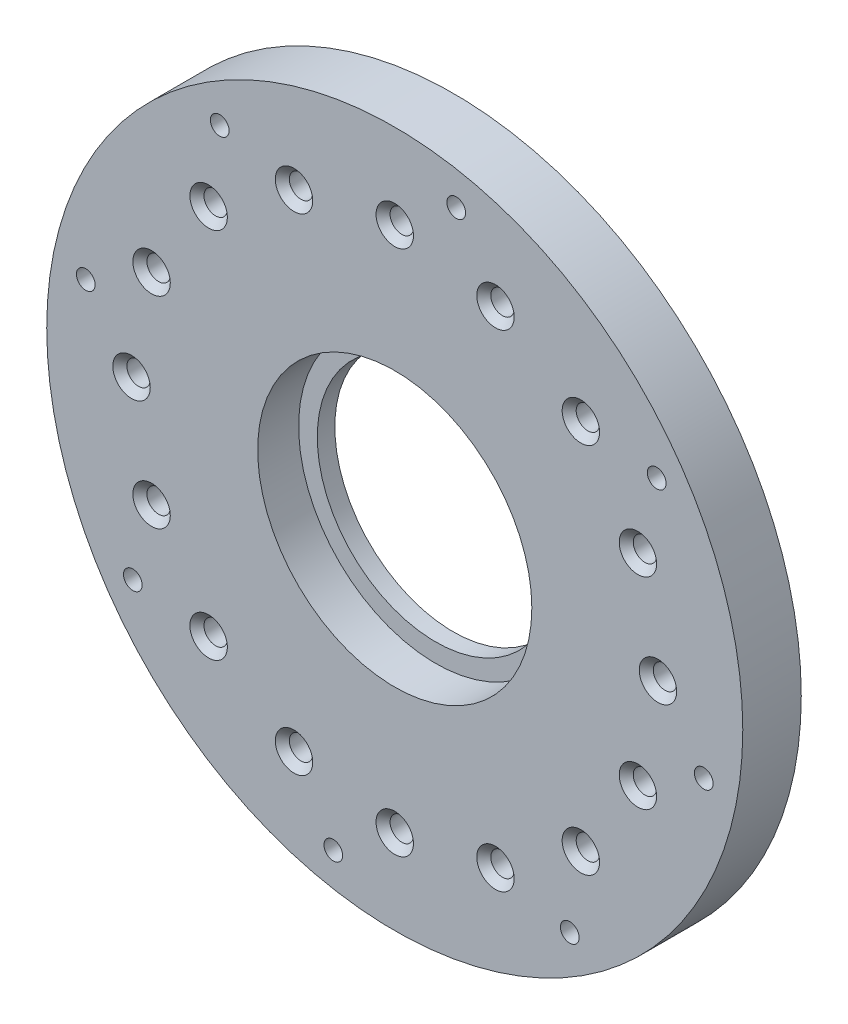
SolidWorks part; units mm, degrees
ref_plane "Front Plane" through (0, 0, 0) normal (0, 0, 1) x (1, 0, 0)
ref_plane "Top Plane" through (0, 0, 0) normal (0, 1, 0) x (1, 0, 0)
ref_plane "Right Plane" through (0, 0, 0) normal (1, 0, 0) x (0, 0, -1)
sketch "Sketch3" plane through (0, 0, 0) normal (0, 0, 1) x (1, 0, 0)
  circle A0 centre (0, 0) radius 59.5
  dimension "D1" = 119
extrude "Boss-Extrude1" add sketch "Sketch3" along normal blind 10
sketch "Sketch4" plane through (0, 0, 10) normal (0, 0, 1) x (1, 0, 0)
  line L0 (0, 0) -> (80.3371, 0) construction
  line L1 (0, 0) -> (65.7826, 43.9545) construction
  circle A0 centre (0, 0) radius 53.86 construction
  circle A1 centre (44.783, 29.923) radius 1.6
  circle A2 centre (52.8251, -10.5076) radius 1.6
  circle A3 centre (29.923, -44.783) radius 1.6
  circle A4 centre (-10.5076, -52.8251) radius 1.6
  circle A5 centre (-44.783, -29.923) radius 1.6
  circle A6 centre (-52.8251, 10.5076) radius 1.6
  circle A7 centre (-29.923, 44.783) radius 1.6
  circle A8 centre (10.5076, 52.8251) radius 1.6
  point P5 (44.783, 29.923)
  point P25 (0, 0)
  dimension "D1" = 107.72
  dimension "D2" = 3.2
  dimension "D3" = 8
extrude "Cut-Extrude1" cut sketch "Sketch4" against normal through all
sketch "Sketch5" plane through (0, 0, 10) normal (0, 0, 1) x (1, 0, 0)
  line L0 (0, 0) -> (91.3259, 0) construction
  circle A0 centre (0, 0) radius 45 construction
  circle A1 centre (45, 0) radius 2
  circle A2 centre (41.5746, -17.2208) radius 2
  circle A3 centre (31.8198, -31.8198) radius 2
  circle A4 centre (17.2208, -41.5746) radius 2
  circle A5 centre (0, -45) radius 2
  circle A6 centre (-17.2208, -41.5746) radius 2
  circle A7 centre (-31.8198, -31.8198) radius 2
  circle A8 centre (-41.5746, -17.2208) radius 2
  circle A9 centre (-45, 0) radius 2
  circle A10 centre (-41.5746, 17.2208) radius 2
  circle A11 centre (-31.8198, 31.8198) radius 2
  circle A12 centre (-17.2208, 41.5746) radius 2
  circle A13 centre (0, 45) radius 2
  circle A14 centre (17.2208, 41.5746) radius 2
  circle A15 centre (31.8198, 31.8198) radius 2
  circle A16 centre (41.5746, 17.2208) radius 2
  point P38 (0, 0)
  dimension "D1" = 90
  dimension "D2" = 4
  dimension "D3" = 16
extrude "Cut-Extrude2" cut sketch "Sketch5" against normal blind 5
sketch "Sketch6" plane through (0, 0, 0) normal (0, 0, -1) x (-1, 0, 0)
  line L0 (0, 0) -> (52.8251, 10.5076) construction
  circle A0 centre (52.8251, 10.5076) radius 2.9
  circle A1 centre (44.783, -29.923) radius 2.9
  circle A2 centre (10.5076, -52.8251) radius 2.9
  circle A3 centre (-29.923, -44.783) radius 2.9
  circle A4 centre (-52.8251, -10.5076) radius 2.9
  circle A5 centre (-44.783, 29.923) radius 2.9
  circle A6 centre (-10.5076, 52.8251) radius 2.9
  circle A7 centre (29.923, 44.783) radius 2.9
  point P22 (0, 0)
  dimension "D1" = 5.8
  dimension "D2" = 8
extrude "Cut-Extrude3" cut sketch "Sketch6" against normal blind 3
sketch "Sketch7" plane through (0, 0, 10) normal (0, 0, 1) x (1, 0, 0)
  circle A0 centre (0, 0) radius 23.435
  dimension "D1" = 46.87
extrude "Cut-Extrude4" cut sketch "Sketch7" against normal blind 7
sketch "Sketch8" plane through (0, 0, 10) normal (0, 0, 1) x (1, 0, 0)
  circle A0 centre (0, 0) radius 20.25
  dimension "D1" = 40.5
extrude "Cut-Extrude5" cut sketch "Sketch8" against normal through all
chamfer "Chamfer1" distance 1.2 angle 45 16 edges at (-39.5746, 17.2208, 10) (-43, 0, 10) (-39.5746, -17.2208, 10) (-29.8198, -31.8198, 10) (-15.2208, -41.5746, 10) (2, -45, 10) (2, 45, 10) (19.2208, -41.5746, 10) (33.8198, -31.8198, 10) (43.5746, -17.2208, 10) (47, 0, 10) (43.5746, 17.2208, 10) (33.8198, 31.8198, 10) (19.2208, 41.5746, 10) (-15.2208, 41.5746, 10) (-29.8198, 31.8198, 10)
